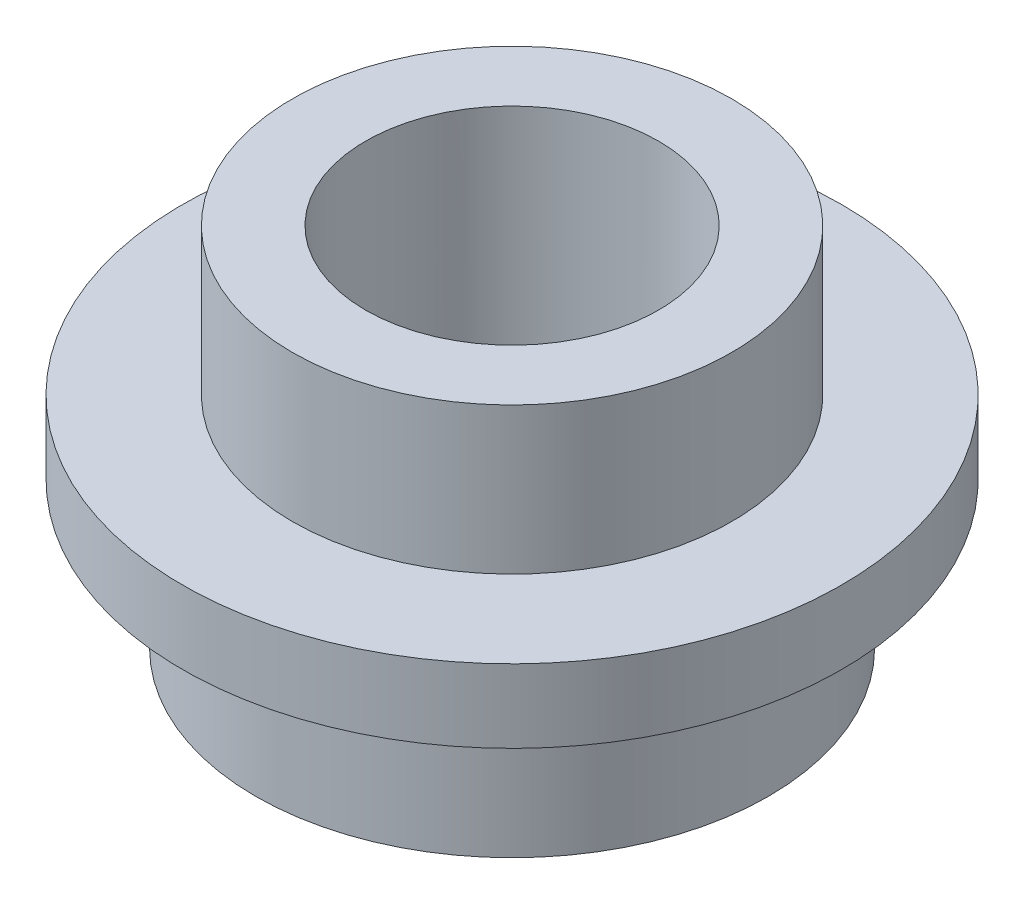
SolidWorks part; units mm, degrees
ref_plane "Front Plane" through (0, 0, 0) normal (0, 0, 1) x (1, 0, 0)
ref_plane "Top Plane" through (0, 0, 0) normal (0, 1, 0) x (1, 0, 0)
ref_plane "Right Plane" through (0, 0, 0) normal (1, 0, 0) x (0, 0, -1)
sketch "Sketch1" plane through (0, 0, 0) normal (0, 1, 0) x (1, 0, 0)
  circle A0 centre (0, 0) radius 19.05
  circle A1 centre (0, 0) radius 12.7
  dimension "D1" = 38.1
  dimension "D2" = 25.4
extrude "Top" add sketch "Sketch1" along normal blind 12.7
sketch "Sketch4" plane through (0, 0, 0) normal (0, -1, 0) x (1, 0, 0)
  circle A0 centre (0, 0) radius 28.575
  circle A1 centre (0, 0) radius 12.7
  dimension "D1" = 57.15
  dimension "D2" = 25.4
extrude "Middle" add sketch "Sketch4" along normal blind 6.35
sketch "Sketch5" plane through (0, -6.35, 0) normal (0, -1, 0) x (1, 0, 0)
  circle A0 centre (0, 0) radius 15.875
  circle A1 centre (0, 0) radius 22.225
  dimension "D1" = 31.75
  dimension "D2" = 44.45
extrude "Bottom" add sketch "Sketch5" along normal blind 12.7
